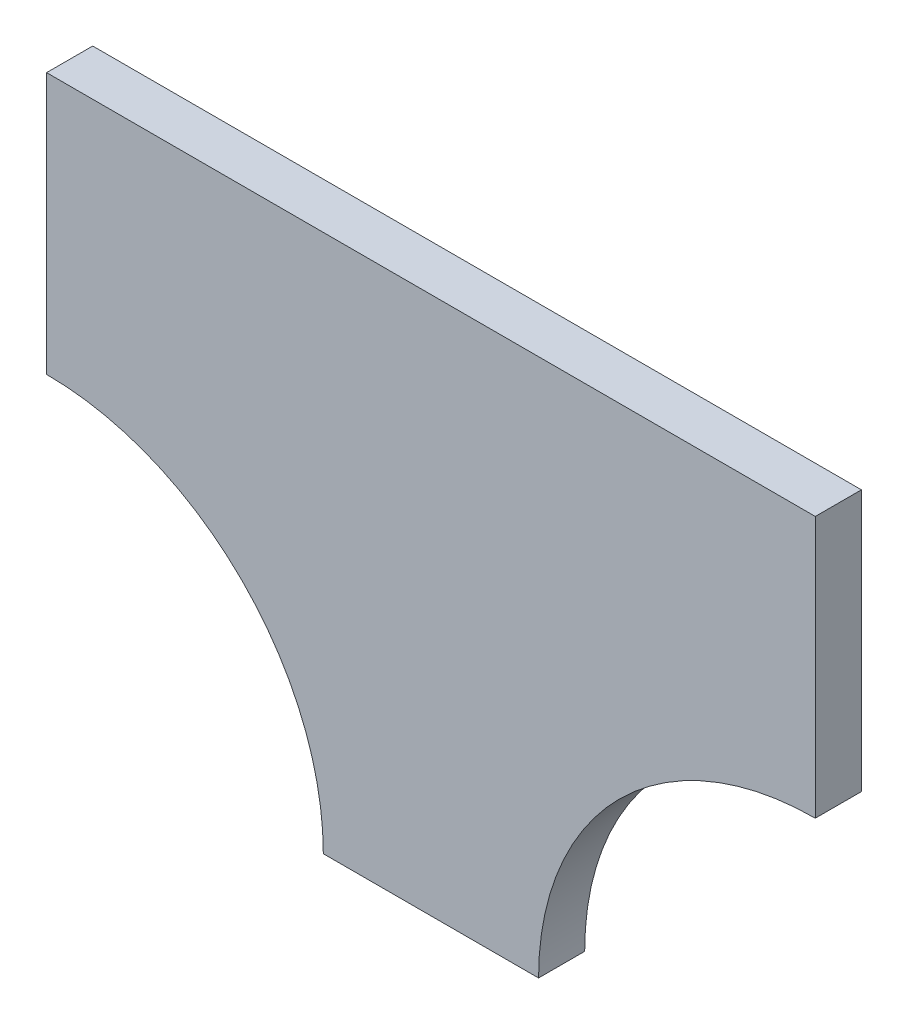
SolidWorks part; units mm, degrees
ref_plane "Front Plane" through (0, 0, 0) normal (0, 0, 1) x (1, 0, 0)
ref_plane "Top Plane" through (0, 0, 0) normal (0, 1, 0) x (1, 0, 0)
ref_plane "Right Plane" through (0, 0, 0) normal (1, 0, 0) x (0, 0, -1)
sketch "Sketch1" plane through (0, 0, 0) normal (0, 0, 1) x (1, 0, 0)
  line L1 (-1000, -700) -> (1000, -700)
  line L2 (-1000, -700) -> (-1000, 700)
  line L3 (-1000, 700) -> (1000, 700)
  line L4 (1000, -700) -> (1000, 700)
  line L5 (0, 700) -> (0, -700) construction
  line L6 (-1000, 0) -> (1000, 0) construction
  circle A0 centre (-1000, -700) radius 720
  circle A1 centre (1000, -700) radius 720
  point P0 (0, 0)
  dimension "D1" = 1400
  dimension "D2" = 2000
extrude "Boss-Extrude1" add sketch "Sketch1" along normal blind 120 contours A1 L4 L3 L2 A0 L1
